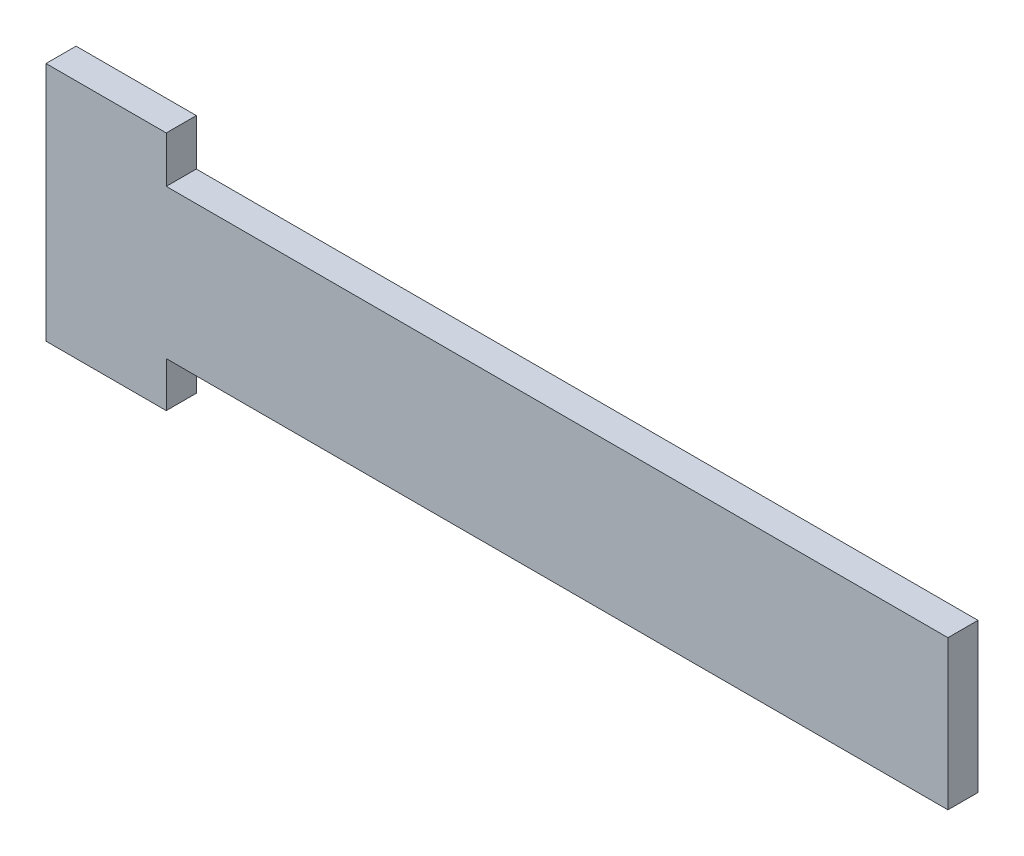
SolidWorks part; units mm, degrees
ref_plane "前视基准面" through (0, 0, 0) normal (0, 0, 1) x (1, 0, 0)
ref_plane "上视基准面" through (0, 0, 0) normal (0, 1, 0) x (1, 0, 0)
ref_plane "右视基准面" through (0, 0, 0) normal (1, 0, 0) x (0, 0, -1)
sketch "草图1" plane through (0, 0, 0) normal (0, 0, 1) x (1, 0, 0)
  line L1 (0, 0) -> (-130, 0)
  line L2 (0, 0) -> (0, 24.8)
  line L3 (0, 24.8) -> (-130, 24.8)
  line L4 (-130, 0) -> (-130, 24.8)
  line L5 (-130, -7.5) -> (-150, -7.5)
  line L6 (-130, -7.5) -> (-130, 32.5)
  line L7 (-130, 32.5) -> (-150, 32.5)
  line L8 (-150, -7.5) -> (-150, 32.5)
  dimension "D1" = 24.8
  dimension "D2" = 130
  dimension "D3" = 40
  dimension "D4" = 7.5
  dimension "D5" = 20
  dimension "D6" = 0
extrude "凸台-拉伸1" add sketch "草图1" along normal blind 5 contours L8 L5 L6 L4 L7 | L4 L1 L2 L3
